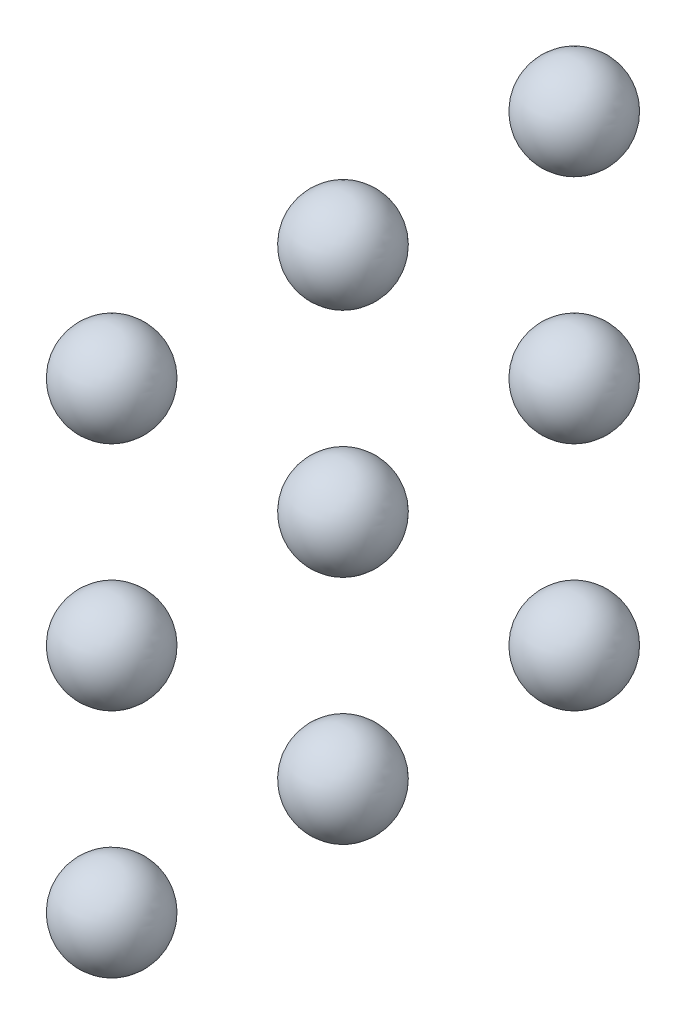
SolidWorks part; units mm, degrees
ref_plane "前视基准面" through (0, 0, 0) normal (0, 0, 1) x (1, 0, 0)
ref_plane "上视基准面" through (0, 0, 0) normal (0, 1, 0) x (1, 0, 0)
ref_plane "右视基准面" through (0, 0, 0) normal (1, 0, 0) x (0, 0, -1)
sketch "草图2" plane through (0, 0, 0) normal (0, 0, 1) x (1, 0, 0)
  line L0 (0, 4) -> (0, -4)
  arc A0 (0, 4) -> (0, -4) centre (0, 0) ccw
  dimension "D1" = 8
revolve "旋转5" add sketch "草图2" angle 360 about L0
pattern_linear "阵列(线性)3" count 3 spacing 20 along (0, 0, 1) count 3 spacing 20 along (0, 1, 0) of bodies 101
